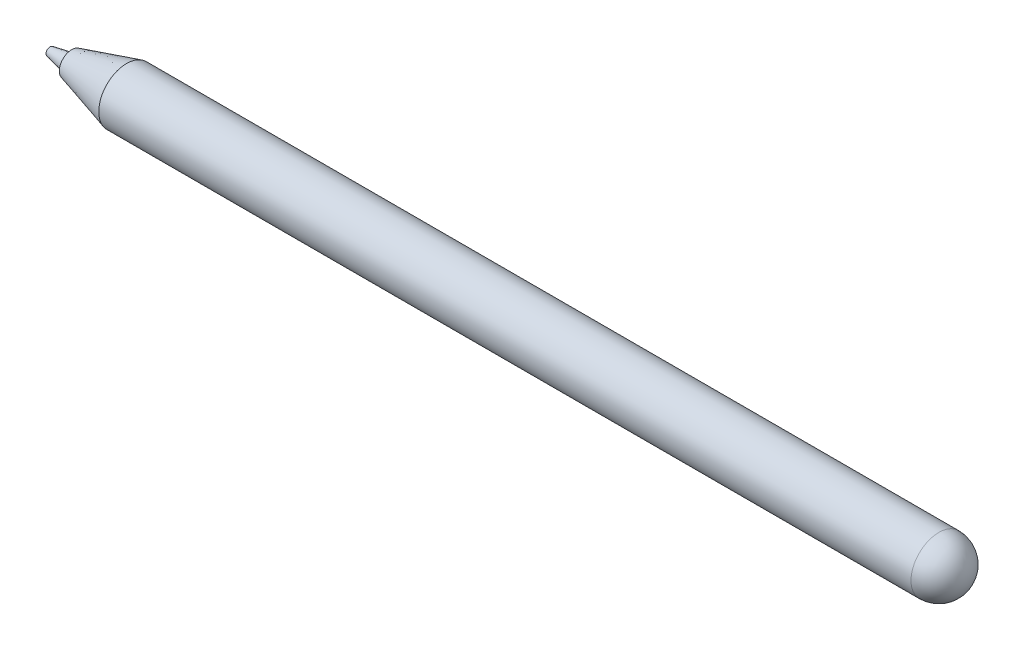
SolidWorks part; units mm, degrees
ref_plane "前视基准面" through (0, 0, 0) normal (0, 0, 1) x (1, 0, 0)
ref_plane "上视基准面" through (0, 0, 0) normal (0, 1, 0) x (1, 0, 0)
ref_plane "右视基准面" through (0, 0, 0) normal (1, 0, 0) x (0, 0, -1)
sketch "草图4" plane through (0, 0, 0) normal (0, 0, 1) x (1, 0, 0)
  line L0 (0, 0) -> (111.8103, 0)
  line L1 (111.8103, 0) -> (111.8103, 24.6977)
  line L2 (111.8103, 24.6977) -> (48.7767, 24.6977)
  line L3 (48.7767, 24.6977) -> (0, 10.9449)
  line L4 (0, 10.9449) -> (0, 0)
revolve "旋转2" add sketch "草图4" angle 360 about L0
sketch "草图6" plane through (0, 0, 0) normal (0, 0, 1) x (1, 0, 0)
  line L0 (0, -0.468) -> (0, 6.9619)
  line L1 (0, 10.9449) -> (0, -10.9449) construction
  line L2 (0, 6.9619) -> (-19.1888, 3.5407)
  line L3 (-19.1888, 3.5407) -> (-19.1888, 0)
  line L4 (-19.1888, 0) -> (0, -0.468)
revolve "旋转3" add sketch "草图6" angle 360 about L4
sketch "草图9" plane through (0, 0, 0) normal (0, 0, 1) x (1, 0, 0)
  line L0 (111.8103, -24.6977) -> (111.8103, 24.6977) construction
  line L1 (111.8103, 24.6977) -> (770.3194, 24.6977)
  line L2 (111.8103, 24.6977) -> (111.8103, 0)
  line L3 (111.8103, 0) -> (770.3194, 0)
  line L4 (770.3194, 24.6977) -> (770.3194, 0)
revolve "旋转4" add sketch "草图9" angle 360 about L3
sketch "草图10" plane through (0, 0, 0) normal (0, 0, 1) x (1, 0, 0)
  line L0 (770.3194, 24.6977) -> (770.3194, 0)
  line L1 (770.3194, -24.6977) -> (770.3194, 24.6977) construction
  line L2 (770.3194, 0) -> (795.0171, 0)
  line L3 (0, 0) -> (795.0171, 0)
  arc A1 (795.0171, 0) -> (770.3194, 24.6977) centre (770.3194, 0) ccw
revolve "旋转5" add sketch "草图10" angle 360 about L3
